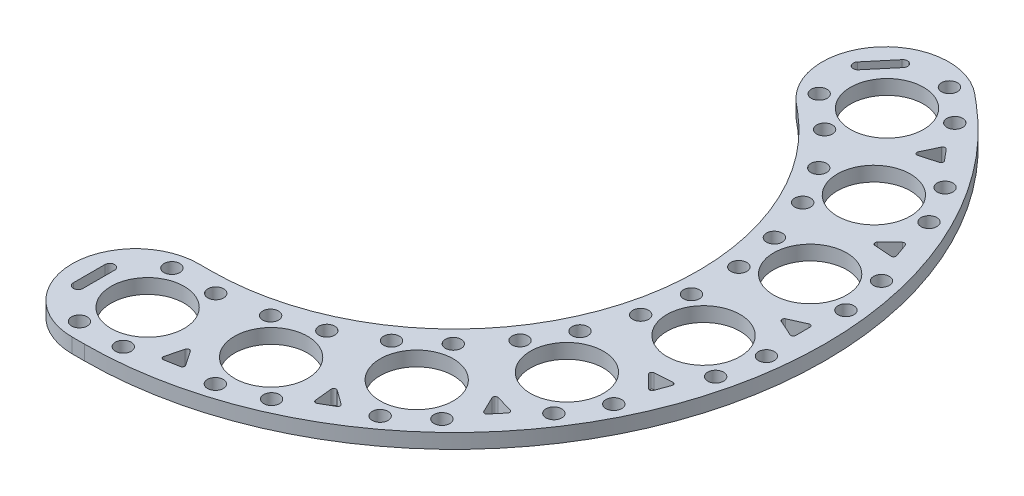
SolidWorks part; units mm, degrees
material "Oak"
ref_plane "Front Plane" through (0, 0, 0) normal (0, 0, 1) x (1, 0, 0)
ref_plane "Top Plane" through (0, 0, 0) normal (0, 1, 0) x (1, 0, 0)
ref_plane "Right Plane" through (0, 0, 0) normal (1, 0, 0) x (0, 0, -1)
sketch "Sketch1" plane through (0, 0, 0) normal (0, 1, 0) x (1, 0, 0)
  line L0 (0, 0) -> (0, -1520) construction
  line L1 (0, -1260) -> (-220, -1260) construction
  line L2 (0, 0) -> (90, -1070.2633) construction
  line L3 (0, 0) -> (450.624, -974.9368) construction
  line L4 (0, 0) -> (642.7876, 766.0444) construction
  line L5 (642.7876, 766.0444) -> (604.4854, 798.1838)
  line L6 (809.9124, 965.216) -> (641.3826, 1106.6293) construction
  line L7 (862.9288, 1168.4136) -> (619.008, 877.7202) construction
  line L8 (977.0372, 1164.3876) -> (938.7349, 1196.5269)
  line L9 (0, -1000) -> (-50, -1000)
  line L10 (0, -1520) -> (-50, -1520)
  line L11 (599.6014, 1056.8364) -> (683.1638, 1156.4222) construction
  line L12 (584.2805, 1069.6921) -> (667.8429, 1169.2779)
  line L13 (614.9223, 1043.9806) -> (698.4847, 1143.5664)
  line L14 (-220, -1195) -> (-220, -1325) construction
  line L15 (-200, -1195) -> (-200, -1325)
  line L16 (-240, -1195) -> (-240, -1325)
  line L17 (1076.4594, 941.8107) -> (1114.4277, 896.5618)
  line L18 (1109.4854, 880.5104) -> (1040.2247, 860.9478)
  line L19 (1028.5012, 874.9193) -> (1059.7936, 939.7308)
  line L20 (0, 0) -> (1018.8391, 854.9075) construction
  line L21 (1265.715, 470.3871) -> (1317.2871, 520.5873)
  line L22 (1333.6592, 516.8418) -> (1353.8617, 461.3358)
  line L23 (1343.7276, 447.9428) -> (1271.9529, 453.2485)
  line L24 (1350.2649, 9.1192) -> (1415.8964, 38.6534)
  line L25 (1430, 29.5341) -> (1430, -29.5341)
  line L26 (1415.8964, -38.6534) -> (1350.2649, -9.1192)
  line L27 (1271.9529, -453.2485) -> (1343.7276, -447.9428)
  line L28 (1353.8617, -461.3358) -> (1333.6592, -516.8418)
  line L29 (1317.2871, -520.5873) -> (1265.715, -470.3871)
  line L30 (1040.2247, -860.9478) -> (1109.4854, -880.5104)
  line L31 (1114.4277, -896.5618) -> (1076.4594, -941.8107)
  line L32 (1059.7936, -939.7308) -> (1028.5012, -874.9193)
  line L33 (683.0299, -1164.8041) -> (741.423, -1206.8755)
  line L34 (740.5773, -1223.6493) -> (689.4227, -1253.1834)
  line L35 (674.4734, -1245.5289) -> (667.235, -1173.9233)
  line L36 (243.4517, -1328.1678) -> (283.9339, -1387.6736)
  line L37 (277.4023, -1403.1465) -> (219.2314, -1413.4036)
  line L38 (207.8017, -1401.0978) -> (225.4904, -1331.3349)
  circle A0 centre (0, 0) radius 1000 construction
  circle A1 centre (0, 0) radius 1520 construction
  circle A2 centre (0, -1260) radius 150
  circle A4 centre (90, -1070.2633) radius 32.5
  circle A7 centre (-90, -1070.2633) radius 32.5
  circle A8 centre (-90, -1449.7367) radius 32.5
  circle A9 centre (90, -1449.7367) radius 32.5
  circle A10 centre (450.624, -974.9368) radius 32.5
  circle A11 centre (430.9454, -1184.0127) radius 150
  circle A12 centre (281.4793, -1036.5004) radius 32.5
  circle A13 centre (580.4115, -1331.525) radius 32.5
  circle A14 centre (411.2668, -1393.0887) radius 32.5
  circle A15 centre (756.896, -762.0184) radius 32.5
  circle A16 centre (809.9124, -965.216) radius 150
  circle A17 centre (619.008, -877.7202) radius 32.5
  circle A18 centre (1000.8168, -1052.7118) radius 32.5
  circle A19 centre (862.9288, -1168.4136) radius 32.5
  circle A20 centre (971.8752, -457.1894) radius 32.5
  circle A21 centre (1091.192, -630) radius 150
  circle A22 centre (881.8752, -613.074) radius 32.5
  circle A23 centre (1300.5088, -646.926) radius 32.5
  circle A24 centre (1210.5088, -802.8106) radius 32.5
  circle A25 centre (1069.632, -97.2166) radius 32.5
  circle A26 centre (1240.8578, -218.7967) radius 150
  circle A27 centre (1038.3753, -274.482) radius 32.5
  circle A28 centre (1443.3402, -163.1114) radius 32.5
  circle A29 centre (1412.0836, -340.3768) radius 32.5
  circle A30 centre (1038.3753, 274.482) radius 32.5
  circle A31 centre (1240.8578, 218.7967) radius 150
  circle A32 centre (1069.632, 97.2166) radius 32.5
  circle A33 centre (1412.0836, 340.3768) radius 32.5
  circle A34 centre (1443.3402, 163.1114) radius 32.5
  circle A35 centre (881.8752, 613.074) radius 32.5
  circle A36 centre (1091.192, 630) radius 150
  circle A37 centre (971.8752, 457.1894) radius 32.5
  circle A38 centre (1210.5088, 802.8106) radius 32.5
  circle A39 centre (1300.5088, 646.926) radius 32.5
  circle A40 centre (619.008, 877.7202) radius 32.5
  circle A41 centre (809.9124, 965.216) radius 150
  circle A42 centre (756.896, 762.0184) radius 32.5
  circle A43 centre (862.9288, 1168.4136) radius 32.5
  circle A44 centre (1000.8168, 1052.7118) radius 32.5
  arc A45 (0, -1000) -> (642.7876, 766.0444) centre (0, 0) ccw
  arc A46 (0, -1520) -> (977.0372, 1164.3876) centre (0, 0) ccw
  arc A47 (604.4854, 798.1838) -> (938.7349, 1196.5269) centre (771.6102, 997.3554) cw
  arc A48 (-50, -1000) -> (-50, -1520) centre (-50, -1260) ccw
  arc A49 (584.2805, 1069.6921) -> (614.9223, 1043.9806) centre (599.6014, 1056.8364) ccw
  arc A50 (698.4847, 1143.5664) -> (667.8429, 1169.2779) centre (683.1638, 1156.4222) ccw
  arc A51 (-200, -1195) -> (-240, -1195) centre (-220, -1195) ccw
  arc A52 (-240, -1325) -> (-200, -1325) centre (-220, -1325) ccw
  arc A53 (1040.2247, 860.9478) -> (1028.5012, 874.9193) centre (1037.5065, 870.5713) cw
  arc A54 (1076.4594, 941.8107) -> (1059.7936, 939.7308) centre (1068.7989, 935.3829) ccw
  arc A55 (1114.4277, 896.5618) -> (1109.4854, 880.5104) centre (1106.7673, 890.1339) cw
  arc A56 (1333.6592, 516.8418) -> (1317.2871, 520.5873) centre (1324.2622, 513.4216) ccw
  arc A57 (1271.9529, 453.2485) -> (1265.715, 470.3871) centre (1272.6902, 463.2213) cw
  arc A58 (1353.8617, 461.3358) -> (1343.7276, 447.9428) centre (1344.4648, 457.9156) cw
  arc A59 (1430, 29.5341) -> (1415.8964, 38.6534) centre (1420, 29.5341) ccw
  arc A60 (1350.2649, -9.1192) -> (1350.2649, 9.1192) centre (1354.3686, 0) cw
  arc A61 (1430, -29.5341) -> (1415.8964, -38.6534) centre (1420, -29.5341) cw
  arc A62 (1353.8617, -461.3358) -> (1343.7276, -447.9428) centre (1344.4648, -457.9156) ccw
  arc A63 (1265.715, -470.3871) -> (1271.9529, -453.2485) centre (1272.6902, -463.2213) cw
  arc A64 (1333.6592, -516.8418) -> (1317.2871, -520.5873) centre (1324.2622, -513.4216) cw
  arc A65 (1114.4277, -896.5618) -> (1109.4854, -880.5104) centre (1106.7673, -890.1339) ccw
  arc A66 (1028.5012, -874.9193) -> (1040.2247, -860.9478) centre (1037.5065, -870.5713) cw
  arc A67 (1076.4594, -941.8107) -> (1059.7936, -939.7308) centre (1068.7989, -935.3829) cw
  arc A68 (740.5773, -1223.6493) -> (741.423, -1206.8755) centre (735.5773, -1214.989) ccw
  arc A69 (667.235, -1173.9233) -> (683.0299, -1164.8041) centre (677.1843, -1172.9176) cw
  arc A70 (689.4227, -1253.1834) -> (674.4734, -1245.5289) centre (684.4227, -1244.5231) cw
  arc A71 (277.4023, -1403.1465) -> (283.9339, -1387.6736) centre (275.6659, -1393.2985) ccw
  arc A72 (225.4904, -1331.3349) -> (243.4517, -1328.1678) centre (235.1836, -1333.7927) cw
  arc A73 (219.2314, -1413.4036) -> (207.8017, -1401.0978) centre (217.495, -1403.5556) cw
  point P6 (0, -1000)
  point P102 (641.3826, 1106.6293)
  point P107 (-220, -1260)
  point P115 (0, 0)
  point P124 (1066.5181, 953.6583)
  point P127 (1124.369, 884.7143)
  point P183 (0, 0)
  dimension "D1" = 2000
  dimension "D2" = 520
  dimension "D3" = 300
  dimension "D4" = 65
  dimension "D5" = 210
  dimension "D11" = 50
  dimension "D14" = 20
  dimension "D16" = 20
  dimension "D22" = 10
  dimension "D6" = 90
  dimension "D7" = 260
  dimension "D8" = 20
  dimension "D9" = 140
  dimension "D12" = 50
  dimension "D13" = 130
  dimension "D15" = 220
  dimension "D17" = 220
  dimension "D18" = 130
  dimension "D19" = 90
  dimension "D20" = 100
  dimension "D21" = 1330
  dimension "D10" = 8
extrude "Boss-Extrude1" add sketch "Sketch1" along normal blind 60
